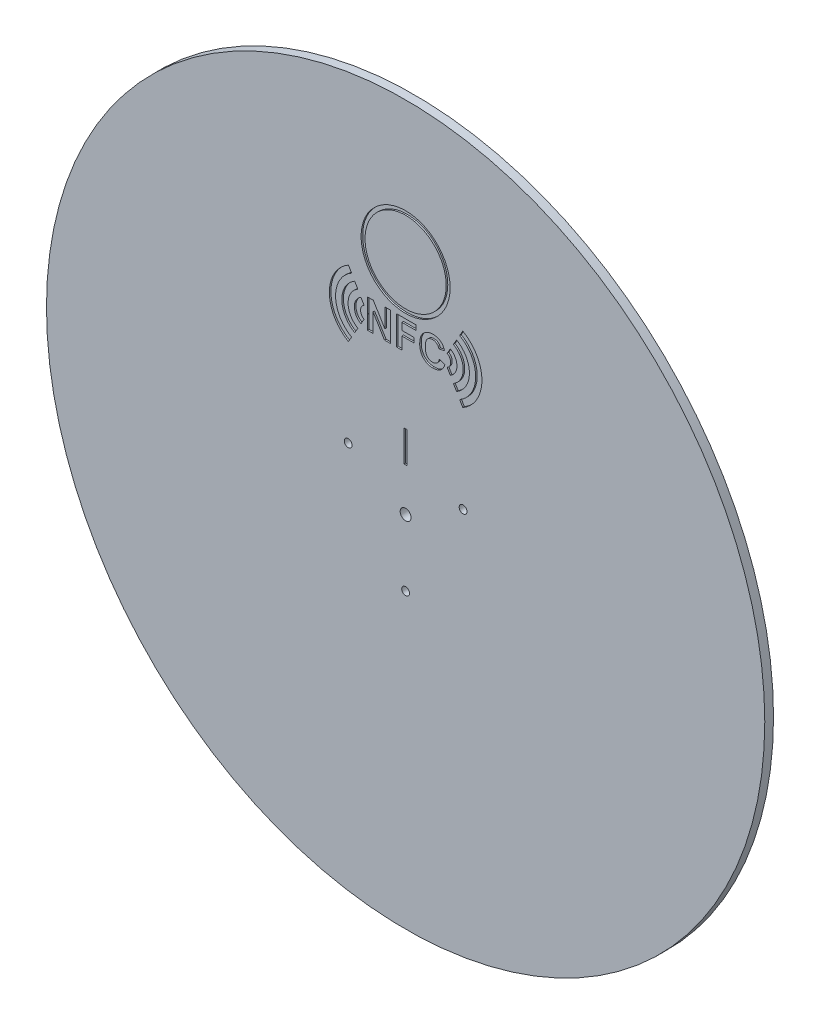
SolidWorks part; units mm, degrees
ref_plane "Front Plane" through (0, 0, 0) normal (0, 0, 1) x (1, 0, 0)
ref_plane "Top Plane" through (0, 0, 0) normal (0, 1, 0) x (1, 0, 0)
ref_plane "Right Plane" through (0, 0, 0) normal (1, 0, 0) x (0, 0, -1)
sketch "Sketch1" plane through (0, 0, 0) normal (0, 0, 1) x (1, 0, 0)
  circle A0 centre (0, 0) radius 115
  circle A1 centre (0, 70) radius 12.6
  circle A2 centre (0, 0) radius 1.75
  dimension "D1" = 25.2
  dimension "D3" = 230
  dimension "D4" = 3.5
  dimension "D2" = 70
extrude "Boss-Extrude1" add sketch "Sketch1" along normal blind 1.2
sketch "Sketch2" plane through (0, 0, 1.2) normal (0, 0, 1) x (1, 0, 0)
  circle A0 centre (0, 0) radius 115
  circle A1 centre (0, 0) radius 1.75
  circle A2 centre (0, 0) radius 1.75 construction
  circle A3 centre (0, 0) radius 115 construction
extrude "Boss-Extrude2" add sketch "Sketch2" along normal blind 0.8
sketch "Sketch3" plane through (0, 0, 2) normal (0, 0, 1) x (1, 0, 0)
  line L0 (-16.9706, 45) -> (16.9706, 45) construction
  line L1 (-12.1796, 49.417) -> (-22.0752, 32.2773)
  line L2 (-12.1796, 49.417) -> (-26.9014, 74.9159)
  line L3 (-12.1796, 49.417) -> (22.1968, 49.417) construction
  line L4 (0, 70) -> (0, 45) construction
  line L5 (12.1796, 49.417) -> (22.0752, 32.2773)
  line L6 (12.1796, 49.417) -> (26.9014, 74.9159)
  line L7 (-12.2094, 45) -> (-12.2094, 54.2459)
  line L8 (-12.2094, 54.2459) -> (-10.3517, 54.2459)
  line L9 (-10.3517, 54.2459) -> (-6.6381, 48.1672)
  line L10 (-6.6381, 48.1672) -> (-6.6381, 54.2459)
  line L11 (-6.6381, 54.2459) -> (-4.86, 54.2459)
  line L12 (-4.86, 54.2459) -> (-4.86, 45)
  line L13 (-4.86, 45) -> (-6.7752, 45)
  line L14 (-6.7752, 45) -> (-10.4313, 50.9825)
  line L15 (-10.4313, 50.9825) -> (-10.4313, 45)
  line L16 (-10.4313, 45) -> (-12.2094, 45)
  line L17 (-2.9634, 45) -> (-2.9634, 54.2459)
  line L18 (-2.9634, 54.2459) -> (3.3191, 54.2459)
  line L19 (3.3191, 54.2459) -> (3.3191, 52.705)
  line L20 (3.3191, 52.705) -> (-1.1854, 52.705)
  line L21 (-1.1854, 52.705) -> (-1.1854, 50.4527)
  line L22 (-1.1854, 50.4527) -> (2.7264, 50.4527)
  line L23 (2.7264, 50.4527) -> (2.7264, 48.9117)
  line L24 (2.7264, 48.9117) -> (-1.1854, 48.9117)
  line L25 (-1.1854, 48.9117) -> (-1.1854, 45)
  line L26 (-1.1854, 45) -> (-2.9634, 45)
  line L27 (10.7869, 48.4376) -> (12.565, 47.8449)
  line L28 (12.4465, 51.6381) -> (10.6684, 51.2825)
  arc A0 (-13.3046, 51.3655) -> (-13.3046, 47.4684) centre (-12.1796, 49.417) ccw
  arc A1 (-14.3046, 53.0976) -> (-14.3046, 45.7364) centre (-12.1796, 49.417) ccw
  arc A2 (-15.3046, 54.8296) -> (-15.3046, 44.0043) centre (-12.1796, 49.417) ccw
  arc A3 (-16.3046, 56.5617) -> (-16.3046, 42.2723) centre (-12.1796, 49.417) ccw
  arc A4 (-17.3046, 58.2938) -> (-17.3046, 40.5402) centre (-12.1796, 49.417) ccw
  arc A5 (-18.3046, 60.0258) -> (-18.3046, 38.8082) centre (-12.1796, 49.417) ccw
  arc A6 (18.3046, 60.0258) -> (18.3046, 38.8082) centre (12.1796, 49.417) cw
  arc A7 (17.3046, 58.2938) -> (17.3046, 40.5402) centre (12.1796, 49.417) cw
  arc A8 (16.3046, 56.5617) -> (16.3046, 42.2723) centre (12.1796, 49.417) cw
  arc A9 (15.3046, 54.8296) -> (15.3046, 44.0043) centre (12.1796, 49.417) cw
  arc A10 (14.3046, 53.0976) -> (14.3046, 45.7364) centre (12.1796, 49.417) cw
  arc A11 (13.3046, 51.3655) -> (13.3046, 47.4684) centre (12.1796, 49.417) cw
  circle A12 centre (0, 70) radius 13
  circle A13 centre (0, 70) radius 14.25
  spline S0 degree 3 poles (12.565, 47.8449) (12.4974, 47.6159) (12.3822, 47.2824) (12.1795, 46.8696) (12.0177, 46.5867) (11.8325, 46.3316) (11.6342, 46.0958) (11.4171, 45.8842) (11.1821, 45.6965) (10.9316, 45.5304) (10.6626, 45.39) (10.3792, 45.2691) (10.0784, 45.1711) (9.7623, 45.0928) (9.3091, 45.0218) (8.9596, 44.9989) (8.7218, 45) knots 0 0 0 0 0.137895 0.202903 0.265168 0.325675 0.384566 0.442764 0.500294 0.557901 0.61591 0.675133 0.73552 0.798252 0.862854 1 1 1 1
  spline S1 degree 3 poles (8.7218, 45) (8.4264, 44.998) (7.9903, 45.0359) (7.432, 45.1668) (7.04, 45.2995) (6.6702, 45.4756) (6.3195, 45.6874) (5.9903, 45.9395) (5.6838, 46.2275) (5.4053, 46.5492) (5.1645, 46.9029) (4.9587, 47.2836) (4.7924, 47.6932) (4.6625, 48.1311) (4.5373, 48.7675) (4.5042, 49.2644) (4.5044, 49.6026) knots 0 0 0 0 0.126019 0.185825 0.244304 0.302279 0.360196 0.418835 0.478842 0.539358 0.600002 0.661055 0.723669 0.788261 0.855679 1 1 1 1
  spline S2 degree 3 poles (4.5044, 49.6026) (4.5038, 49.9594) (4.5381, 50.481) (4.6601, 51.15) (4.7902, 51.606) (4.9541, 52.0324) (5.1601, 52.4248) (5.3985, 52.7885) (5.6757, 53.1169) (5.9837, 53.4085) (6.3136, 53.6663) (6.6687, 53.8826) (7.047, 54.0595) (7.449, 54.1963) (8.0264, 54.3308) (8.4788, 54.3619) (8.7848, 54.3645) knots 0 0 0 0 0.147853 0.216063 0.281514 0.344147 0.40504 0.464872 0.524079 0.582725 0.640362 0.697329 0.754684 0.813113 0.873015 1 1 1 1
  spline S3 degree 3 poles (8.7848, 54.3645) (9.0521, 54.3617) (9.4475, 54.3377) (9.9527, 54.228) (10.3058, 54.1195) (10.6383, 53.9761) (11.0566, 53.7426) (11.3387, 53.5188) (11.5111, 53.3532) knots 0 0 0 0 0.269222 0.396222 0.51914 0.640112 0.759624 1 1 1 1
  spline S4 degree 3 poles (11.5111, 53.3532) (11.6189, 53.2521) (11.7654, 53.0814) (11.9392, 52.8317) (12.0623, 52.6256) (12.172, 52.401) (12.3112, 52.0744) (12.397, 51.8163) (12.4465, 51.6381) knots 0 0 0 0 0.223923 0.340367 0.461367 0.587913 0.71931 1 1 1 1
  spline S5 degree 3 poles (10.6684, 51.2825) (10.6412, 51.3981) (10.5879, 51.5656) (10.4942, 51.7774) (10.4086, 51.9218) (10.3176, 52.0603) (10.2099, 52.1868) (10.0924, 52.3047) (9.9641, 52.4126) (9.8267, 52.5084) (9.6827, 52.5946) (9.5296, 52.6649) (9.3694, 52.7219) (9.2028, 52.7695) (8.966, 52.8099) (8.7842, 52.8264) (8.6607, 52.8235) knots 0 0 0 0 0.129415 0.191523 0.252186 0.31235 0.372124 0.433096 0.493819 0.554747 0.61575 0.676633 0.738217 0.801142 0.865493 1 1 1 1
  spline S6 degree 3 poles (8.6607, 52.8235) (8.4915, 52.8261) (8.2426, 52.7998) (7.9226, 52.7271) (7.6997, 52.6461) (7.4907, 52.5424) (7.2933, 52.4163) (7.1085, 52.2684) (6.9362, 52.0969) (6.7816, 51.8988) (6.6457, 51.6735) (6.5329, 51.4187) (6.4414, 51.1366) (6.3694, 50.8268) (6.298, 50.3592) (6.2853, 49.9911) (6.2825, 49.7378) knots 0 0 0 0 0.114442 0.169048 0.221995 0.274768 0.326889 0.380477 0.434921 0.491257 0.55039 0.612762 0.67972 0.751074 0.828129 1 1 1 1
  spline S7 degree 3 poles (6.2825, 49.7378) (6.2853, 49.4703) (6.2976, 49.0825) (6.3696, 48.5897) (6.4407, 48.2649) (6.5327, 47.9706) (6.6452, 47.7074) (6.779, 47.475) (6.9339, 47.2735) (7.1059, 47.1004) (7.2903, 46.9516) (7.4862, 46.8243) (7.6946, 46.7196) (7.9163, 46.6405) (8.2331, 46.5621) (8.4813, 46.5399) (8.6496, 46.541) knots 0 0 0 0 0.177656 0.256733 0.330177 0.398063 0.460995 0.519731 0.575527 0.629114 0.681254 0.732498 0.783792 0.835623 0.888379 1 1 1 1
  spline S8 degree 3 poles (8.6496, 46.541) (8.7745, 46.5428) (8.9609, 46.5521) (9.2008, 46.6033) (9.3717, 46.6533) (9.5367, 46.7161) (9.6934, 46.7965) (9.8446, 46.889) (9.9874, 46.9974) (10.1237, 47.1191) (10.2479, 47.2597) (10.3632, 47.416) (10.468, 47.5888) (10.5658, 47.7768) (10.6801, 48.0588) (10.7505, 48.282) (10.7869, 48.4376) knots 0 0 0 0 0.120461 0.178741 0.235724 0.291792 0.348406 0.404979 0.462271 0.52076 0.580529 0.642578 0.707405 0.77492 0.84633 1 1 1 1
  point P3 (0, 45)
  dimension "D2" = 2
  dimension "D3" = 2
  dimension "D4" = 2
  dimension "D5" = 2
  dimension "D6" = 2
  dimension "D7" = 4.5
  dimension "D10" = 26
  dimension "D11" = 1.25
  dimension "D1" = 45
  dimension "D8" = 120
  dimension "D9" = 120
extrude "Cut-Extrude1" cut sketch "Sketch3" against normal blind 0.5 contours L16 L15 L14 L13 L12 L11 L10 L9 L8 L7 L2 L1 | L26 L25 L24 L23 L22 L21 L20 L19 L18 L17 | S8 S7 S6 S5 L28 S4 S3 S2 S1 S0 L27 | L6 A11 L5 A10 | L6 A9 L5 A8 | L6 A7 L5 A6 | L2 A1 L1 A0 | L2 A3 L1 A2 | L2 A5 L1 A4 | A13 | A12
sketch "Sketch4" plane through (0, 0, 0) normal (0, 0, -1) x (-1, 0, 0)
  circle A0 centre (0, 0) radius 115
  circle A1 centre (0, 0) radius 1.75
  circle A2 centre (0, 0) radius 1.75 construction
  circle A3 centre (0, 0) radius 115 construction
extrude "Boss-Extrude3" add sketch "Sketch4" along normal blind 0.8
sketch "Sketch5" plane through (0, 0, 2) normal (0, 0, 1) x (1, 0, 0)
  line L1 (-0.5, 23.75) -> (0.5, 23.75)
  line L2 (-0.5, 23.75) -> (-0.5, 13.75)
  line L3 (-0.5, 13.75) -> (0.5, 13.75)
  line L4 (0.5, 23.75) -> (0.5, 13.75)
  circle A0 centre (0, -21.25) radius 1.25
  circle A1 centre (-18.403, 10.625) radius 1.25
  circle A2 centre (18.403, 10.625) radius 1.25
  circle A3 centre (0, 0) radius 1.75 construction
  point P14 (0, 0)
  dimension "D2" = 2.5
  dimension "D1" = 21.25
  dimension "D4" = 1
  dimension "D5" = 10
  dimension "D3" = 0.5
  dimension "D6" = 35
  dimension "D7" = 3
extrude "Cut-Extrude2" cut sketch "Sketch5" against normal up to surface (2.8 mm away) contours L2 L1 L4 L3 | A2 | A1 | A0 up to face at (-115, 0, -0.8)
sketch "Sketch6" plane through (0, 0, -0.8) normal (0, 0, -1) x (-1, 0, 0)
  line L1 (-0.5, 23.75) -> (0.5, 23.75)
  line L2 (-0.5, 23.75) -> (-0.5, 13.75)
  line L3 (-0.5, 13.75) -> (0.5, 13.75)
  line L4 (0.5, 23.75) -> (0.5, 13.75)
extrude "Boss-Extrude4" add sketch "Sketch6" against normal up to surface (2.3 mm away) up to face at (9.4165, 50.0138, 1.5)
